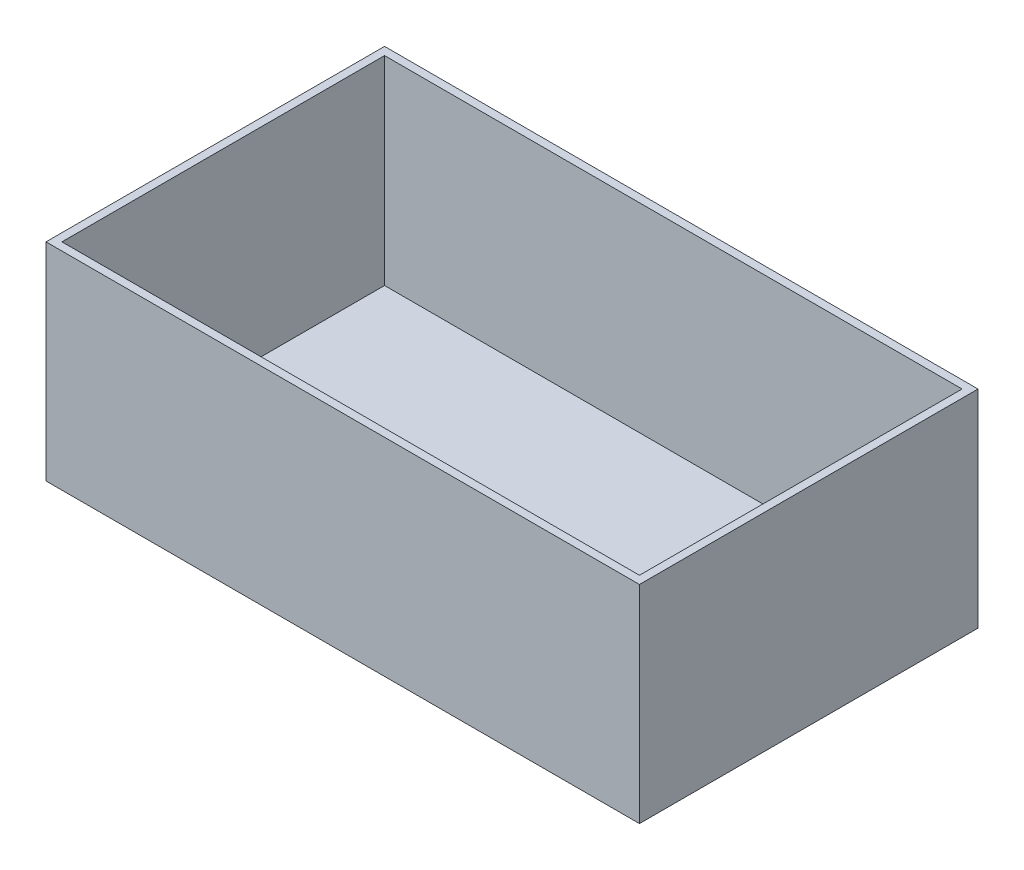
SolidWorks part; units mm, degrees
ref_plane "Front" through (0, 0, 0) normal (0, 0, 1) x (1, 0, 0)
ref_plane "Top" through (0, 0, 0) normal (0, 1, 0) x (1, 0, 0)
ref_plane "Right" through (0, 0, 0) normal (1, 0, 0) x (0, 0, -1)
sketch "Sketch1" plane through (0, 0, 0) normal (0, 1, 0) x (1, 0, 0)
  line L0 (-72.5, 40.5) -> (72.5, -40.5) construction
  line L1 (-72.5, 40.5) -> (72.5, 40.5) construction
  line L2 (-72.5, 40.5) -> (-72.5, -40.5) construction
  line L3 (-72.5, -40.5) -> (72.5, -40.5) construction
  line L4 (72.5, 40.5) -> (72.5, -40.5) construction
  line L5 (-74.5, 42.5) -> (-74.5, -42.5)
  line L6 (-74.5, -42.5) -> (74.5, -42.5)
  line L7 (74.5, 42.5) -> (74.5, -42.5)
  line L8 (-74.5, 42.5) -> (74.5, 42.5)
  dimension "D1" = 145
  dimension "D2" = 81
  dimension "D3" = 2
extrude "Boss-Extrude1" add sketch "Sketch1" along normal blind 2
sketch "Sketch2" plane through (0, 2, 0) normal (0, 1, 0) x (1, 0, 0)
  line L0 (72.5, 40.5) -> (-72.5, 40.5)
  line L1 (-72.5, 40.5) -> (-72.5, -40.5)
  line L2 (-72.5, -40.5) -> (72.5, -40.5)
  line L3 (72.5, -40.5) -> (72.5, 40.5)
  line L4 (74.5, 42.5) -> (-74.5, 42.5)
  line L5 (-74.5, 42.5) -> (-74.5, -42.5)
  line L6 (-74.5, -42.5) -> (74.5, -42.5)
  line L7 (74.5, -42.5) -> (74.5, 42.5)
  line L8 (74.5, 42.5) -> (-74.5, 42.5)
  line L9 (-74.5, 42.5) -> (-74.5, -42.5)
  line L10 (-74.5, -42.5) -> (74.5, -42.5)
  line L11 (74.5, -42.5) -> (74.5, 42.5)
  dimension "D1" = 0
  dimension "D2" = 2
extrude "Boss-Extrude2" add sketch "Sketch2" along normal blind 50
